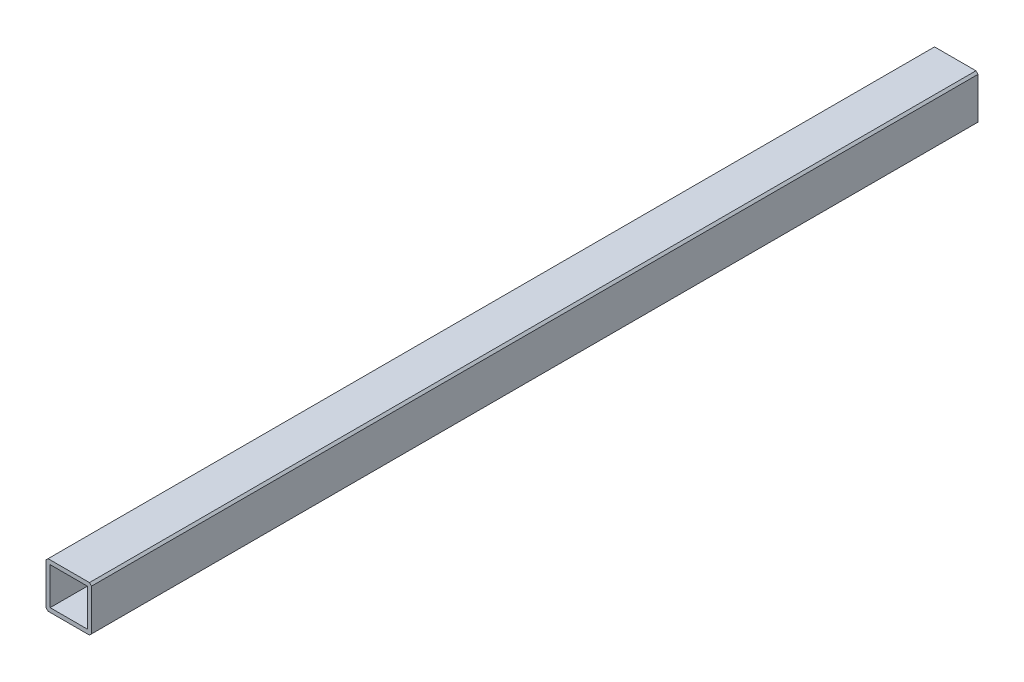
SolidWorks part; units mm, degrees
material "7075-T6, Piastra (SS)"
ref_plane "Piano frontale" through (0, 0, 0) normal (0, 0, 1) x (1, 0, 0)
ref_plane "Piano superiore" through (0, 0, 0) normal (0, 1, 0) x (1, 0, 0)
ref_plane "Piano destro" through (0, 0, 0) normal (1, 0, 0) x (0, 0, -1)
sketch "Schizzo1" plane through (0, 0, 0) normal (0, 0, 1) x (1, 0, 0)
  line L0 (0, 11) -> (0, 0)
  line L1 (0, 0) -> (11, 0)
  line L2 (0, 11) -> (11, 11)
  line L3 (11, 11) -> (11, 0)
  dimension "D1" = 11
  dimension "D2" = 11
extrude "Extrude-Thin1" add sketch "Schizzo1" along normal up to surface (214.16 mm away) thin thin type one direction reverse wall 1
chamfer "Chamfer1" distance 0.5 angle 45 4 edges at (11, 0, 107.08) (11, 11, 107.08) (0, 0, 107.08) (0, 11, 107.08)
sketch "Sketch1" plane through (0, 0, 0) normal (-1, 0, 0) x (0, 0, 1)
  line L4 (0, 10.5) -> (0, 0.5)
  line L5 (0, 0.5) -> (214.16, 0.5)
  line L6 (214.16, 0.5) -> (214.16, 10.5)
  line L7 (214.16, 10.5) -> (0, 10.5)
  line L8 (0, 10.5) -> (0, 0.5)
  line L9 (0, 0.5) -> (214.16, 0.5)
  line L10 (214.16, 0.5) -> (214.16, 10.5)
  line L11 (214.16, 10.5) -> (0, 10.5)
  dimension "D1" = 0
